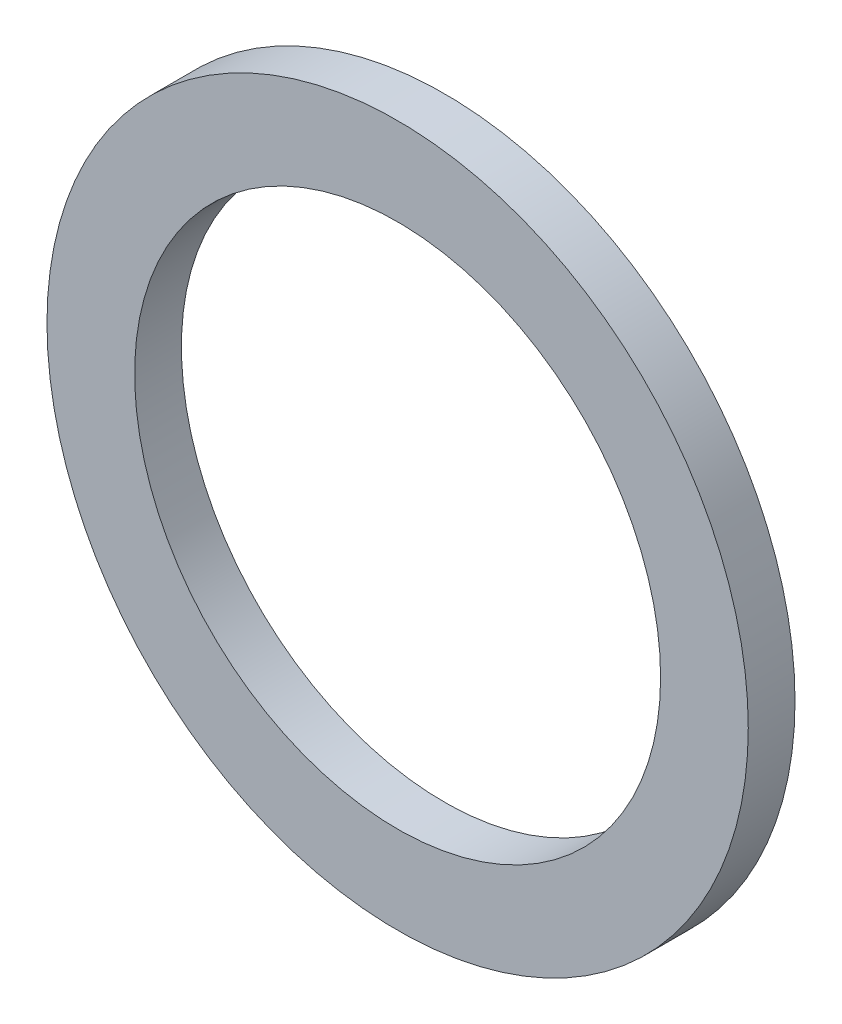
SolidWorks part; units mm, degrees
ref_plane "Plan de face" through (0, 0, 0) normal (0, 0, 1) x (1, 0, 0)
ref_plane "Plan de dessus" through (0, 0, 0) normal (0, 1, 0) x (1, 0, 0)
ref_plane "Plan de droite" through (0, 0, 0) normal (1, 0, 0) x (0, 0, -1)
sketch "Esquisse1" plane through (0, 0, 0) normal (0, 0, 1) x (1, 0, 0)
  circle A0 centre (0, 0) radius 2.25
  circle A1 centre (0, 0) radius 3
  dimension "D1" = 4.5
  dimension "D2" = 6
extrude "Boss.-Extru.1" add sketch "Esquisse1" along normal blind 0.4
